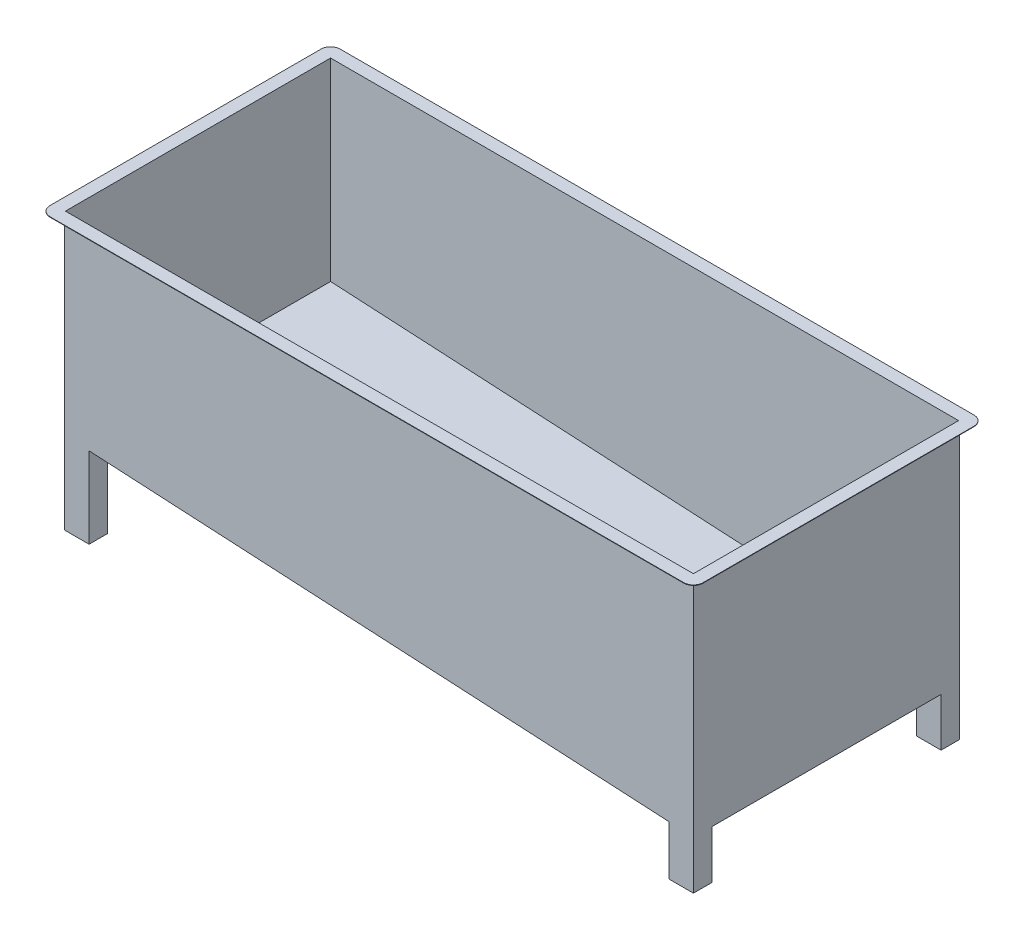
SolidWorks part; units mm, degrees
ref_plane "Alzado" through (0, 0, 0) normal (0, 0, 1) x (1, 0, 0)
ref_plane "Planta" through (0, 0, 0) normal (0, 1, 0) x (1, 0, 0)
ref_plane "Vista lateral" through (0, 0, 0) normal (1, 0, 0) x (0, 0, -1)
sketch "Croquis2" plane through (0, 0, 0) normal (0, 1, 0) x (1, 0, 0)
  line L1 (-1300, -550) -> (1300, -550)
  line L2 (-1300, -550) -> (-1300, 550)
  line L3 (-1300, 550) -> (1300, 550)
  line L4 (1300, -550) -> (1300, 550)
  line L5 (-1300, -550) -> (1300, 550) construction
  line L6 (-1300, 550) -> (1300, -550) construction
  point P0 (0, 0)
  dimension "D1" = 1100
  dimension "D2" = 2600
extrude "Saliente-Extruir1" add sketch "Croquis2" along normal blind 1.89
sketch "Croquis3" plane through (0, 1.89, 0) normal (0, 1, 0) x (1, 0, 0)
  line L1 (-1298.11, 548.11) -> (-1298.11, -548.11)
  line L2 (-1300, 550) -> (1300, 550)
  line L3 (-1300, 550) -> (-1300, -550)
  line L4 (-1300, -550) -> (1300, -550)
  line L5 (1300, 550) -> (1300, -550)
  line L6 (-1298.11, -548.11) -> (1298.11, -548.11)
  line L7 (1298.11, 548.11) -> (1298.11, -548.11)
  line L8 (-1298.11, 548.11) -> (1298.11, 548.11)
  dimension "D1" = 1.89
extrude "Saliente-Extruir2" add sketch "Croquis3" along normal blind 940
sketch "Croquis4" plane through (0, 941.89, 0) normal (0, 1, 0) x (1, 0, 0)
  line L0 (-1350, 600) -> (-1350, -600)
  line L1 (-1300, 550) -> (1300, 550)
  line L2 (-1300, 550) -> (-1300, -550)
  line L3 (-1300, -550) -> (1300, -550)
  line L4 (1300, 550) -> (1300, -550)
  line L5 (-1350, -600) -> (1350, -600)
  line L6 (1350, 600) -> (1350, -600)
  line L7 (-1350, 600) -> (1350, 600)
  dimension "D1" = 50
extrude "Saliente-Extruir3" add sketch "Croquis4" against normal blind 1.89
fillet "Redondeo1" radius 40 4 edges at (-1350, 940.945, -600) (-1350, 940.945, 600) (1350, 940.945, -600) (1350, 940.945, 600)
sketch "Croquis6" plane through (0, 0, -550) normal (0, 0, -1) x (-1, 0, 0)
  line L0 (-1300, 0) -> (1300, 140)
  line L1 (1300, 940) -> (1300, 0) construction
  line L2 (1300, 140) -> (1300, 0)
  line L3 (1300, 0) -> (-1300, 0)
  dimension "D1" = 140
extrude "Cortar-Extruir2" cut sketch "Croquis6" against normal up to surface (1100 mm away) up to face at (0, 470, 550)
sketch "Croquis7" plane through (0, 0, -550) normal (0, 0, -1) x (-1, 0, 0)
  line L0 (-1300, 0) -> (1300, 140)
  line L1 (-1300, 1.8927) -> (1300, 141.8927)
  line L2 (-1300, 0) -> (-1300, 1.8927)
  line L4 (1300, 140) -> (1300, 141.8927)
  dimension "D1" = 1.89
extrude "Saliente-Extruir4" add sketch "Croquis7" against normal up to surface (1100 mm away) up to face at (0, 505, 550)
sketch "Croquis8" plane through (0, 0, -550) normal (0, 0, -1) x (-1, 0, 0)
  line L0 (-1300, 0) -> (-1300, -200)
  line L1 (-1300, -200) -> (-1198.4, -200)
  line L2 (-1198.4, -200) -> (-1198.4, 5.4708)
  line L3 (-1300, 0) -> (-1198.4, 5.4708)
  line L5 (-1198.4, -200) -> (1198.4, -200) construction
  line L6 (1300, 140) -> (1300, -200)
  line L7 (1198.4, -200) -> (1300, -200)
  line L8 (1198.4, -200) -> (1198.4, 134.5292)
  line L9 (1300, 140) -> (1198.4, 134.5292)
  dimension "D1" = 200
  dimension "D2" = 101.6
  dimension "D3" = 101.6
extrude "Saliente-Extruir5" add sketch "Croquis8" against normal blind 76.2
sketch "Croquis9" plane through (0, 0, 550) normal (0, 0, 1) x (1, 0, 0)
  line L0 (1300, 0) -> (1300, -200)
  line L1 (1300, -200) -> (1198.4, -200)
  line L2 (1198.4, -200) -> (1198.4, 5.4708)
  line L3 (1300, 0) -> (-1300, 140) construction
  line L4 (1198.4, 5.4708) -> (1300, 0) construction
  line L5 (1198.4, 5.4708) -> (1300, 0)
  line L6 (-1300, 140) -> (-1300, -200)
  line L7 (-1300, -200) -> (-1198.4, -200)
  line L8 (-1198.4, -200) -> (-1198.4, 134.5292)
  line L9 (-1198.4, 134.5292) -> (-1300, 140)
extrude "Saliente-Extruir6" add sketch "Croquis9" against normal blind 76.2
sketch "Croquis10" plane through (0, -200, 0) normal (0, -1, 0) x (1, 0, 0)
  line L0 (-1198.4, -550) -> (1198.4, -550) construction
  line L1 (1300, 550) -> (1300, -550) construction
  line L2 (1250, 0) -> (1250, 300) construction
  circle A0 centre (1250, 0) radius 12.7
  circle A1 centre (1250, 300) radius 12.7
  dimension "D1" = 25.4
  dimension "D3" = 50
  dimension "D4" = 25.4
  dimension "D2" = 550
  dimension "D5" = 300
extrude "Cortar-Extruir3" cut sketch "Croquis10" against normal blind 280
